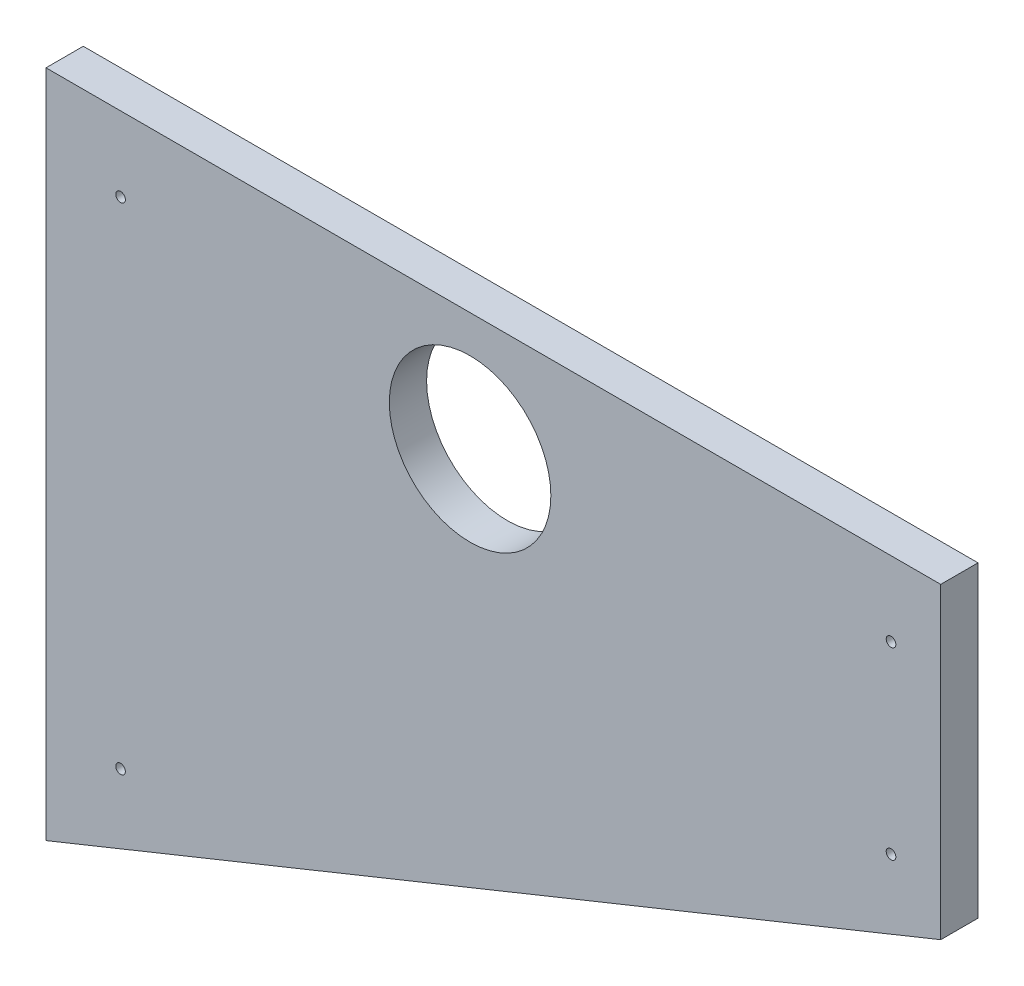
SolidWorks part; units mm, degrees
material "Beech"
ref_plane "Front Plane" through (0, 0, 0) normal (0, 0, 1) x (1, 0, 0)
ref_plane "Top Plane" through (0, 0, 0) normal (0, 1, 0) x (1, 0, 0)
ref_plane "Right Plane" through (0, 0, 0) normal (1, 0, 0) x (0, 0, -1)
sketch "Sketch1" plane through (0, 0, 0) normal (0, 0, 1) x (1, 0, 0)
  line L0 (2683.51, 6641.7419) -> (3140.71, 6826.4627) construction
  line L1 (2683.51, 7002.78) -> (2683.51, 5935.98) construction
  line L8 (2683.51, 6983.73) -> (2683.51, 6641.7419)
  line L9 (2683.51, 6641.7419) -> (3140.71, 6826.4627)
  line L10 (3140.71, 6826.4627) -> (3140.71, 6983.73)
  line L11 (3140.71, 6983.73) -> (2683.51, 6983.73)
extrude "Boss-Extrude1" add sketch "Sketch1" along normal blind 19.05
hole_wizard "CSK for #8 Flat Head Machine Screw (100)1" positions "Sketch2" profile "Sketch3" countersink size "#8" standard "ANSI Inch" end condition through all
sketch "Sketch2" plane through (0, 0, 0) normal (0, 0, -1) x (0, 1, 0)
  point P0 (6692.5419, 2721.61)
  point P1 (6945.63, 2721.61)
  point P2 (6945.63, 3115.31)
  point P3 (6851.607, 3115.31)
sketch "Sketch3" plane through (2721.61, 6692.5419, 0) normal (1, 0, 0) x (0, 1, 0)
  line L0 (0, 0) -> (0, 19.05)
  line L1 (0, 19.05) -> (2.4574, 19.05)
  line L2 (2.4574, 19.05) -> (2.4574, 1.4759)
  line L3 (2.4574, 1.4759) -> (4.2164, 0)
  line L4 (4.2164, 0) -> (0, 0)
  line L5 (-2.4574, 1.4759) -> (-4.2164, 0) construction
  line L6 (0, -6.35) -> (0, 107.95) construction
  dimension "Thru Hole Dia." = 4.9149
  dimension "Thru Hole Depth" = 19.05
  dimension "Near C'Sink Dia." = 8.4328
  dimension "Near C'Sink Angle" = 100
sketch "Sketch4" plane through (0, 0, 0) normal (0, 0, -1) x (-1, 0, 0)
  line L1 (-2892.3702, 6875.0245) -> (-2939.4712, 6894.0546) construction
  line L2 (-2888.2288, 6885.275) -> (-2896.5117, 6864.7741) construction
  line L3 (-2960.2639, 6842.5908) -> (-2941.3977, 6889.2862) construction
  line L4 (-2915.9207, 6884.5395) -> (-2875.8452, 6983.73) construction
  line L5 (-2937.51, 6983.73) -> (-2810.51, 6983.73) construction
  line L6 (-3061.335, 6964.68) -> (-2940.685, 6964.68) construction
  circle A0 centre (-2900.218, 6923.405) radius 41.275
  dimension "D1" = 82.55
extrude "Cut-Extrude1" cut sketch "Sketch4" against normal up to vertex (19.05 mm away)
